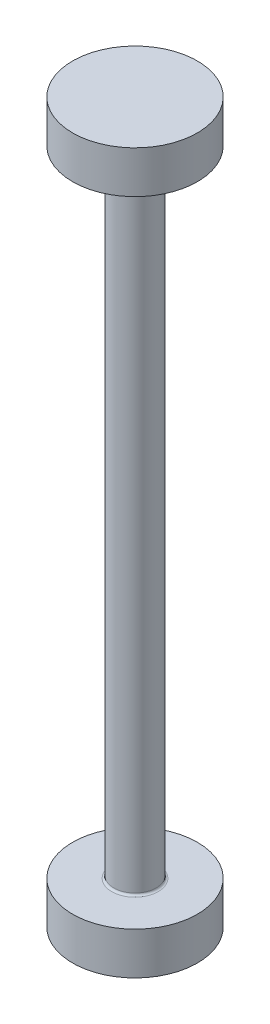
SolidWorks part; units mm, degrees
ref_plane "前视基准面" through (0, 0, 0) normal (0, 0, 1) x (1, 0, 0)
ref_plane "上视基准面" through (0, 0, 0) normal (0, 1, 0) x (1, 0, 0)
ref_plane "右视基准面" through (0, 0, 0) normal (1, 0, 0) x (0, 0, -1)
other "Configuration Table"
sketch "草图1" plane through (0, 1690.1012, 0) normal (0, -1, 0) x (1, 0, 0)
  circle A0 centre (0, 0) radius 29.5
  dimension "D1" = 59
extrude "凸台-拉伸1" add sketch "草图1" against normal blind 20
sketch "草图3" plane through (0, 1710.1012, 0) normal (0, 1, 0) x (1, 0, 0)
  circle A0 centre (0, 0) radius 10
  dimension "D1" = 20
extrude "凸台-拉伸2" add sketch "草图3" along normal blind 300
sketch "草图4" plane through (0, 2010.1012, 0) normal (0, 1, 0) x (1, 0, 0)
  circle A0 centre (0, 0) radius 29.5
extrude "凸台-拉伸3" add sketch "草图4" along normal blind 20
fillet "圆角1" radius 1 2 edges at (0, 1710.1012, 10) (0, 2010.1012, 10)
